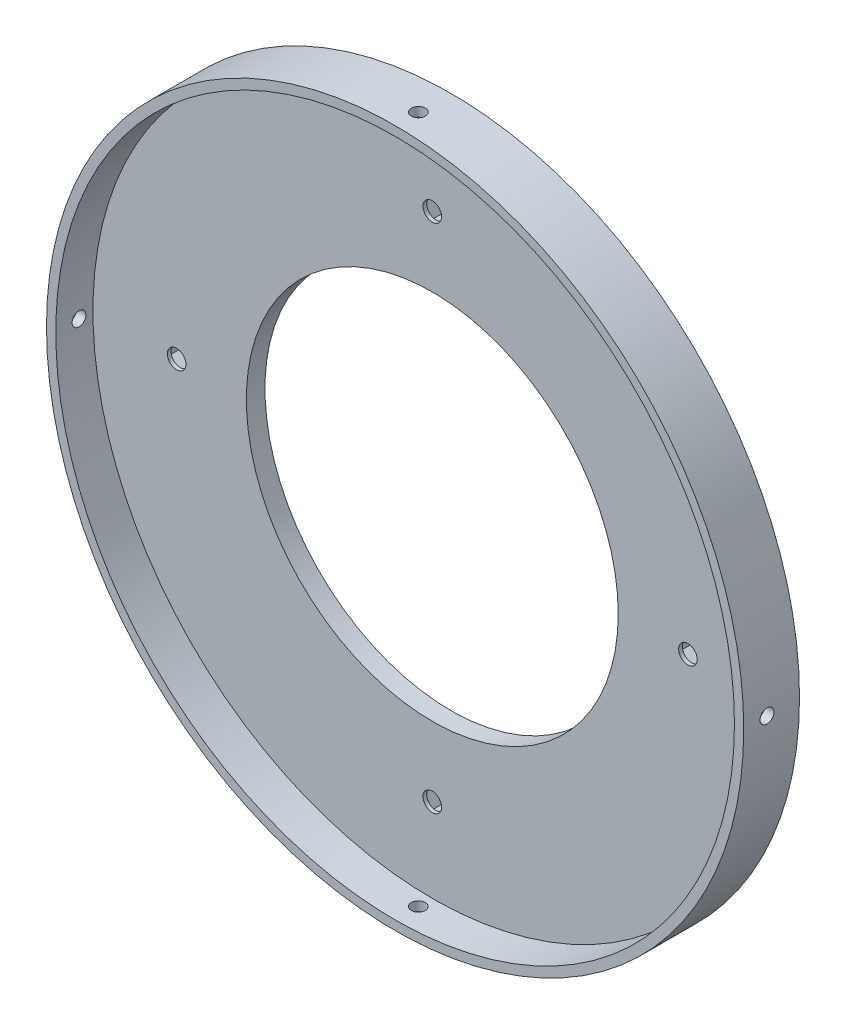
SolidWorks part; units mm, degrees
material "PET"
ref_plane "Front Plane" through (0, 0, 0) normal (0, 0, 1) x (1, 0, 0)
ref_plane "Top Plane" through (0, 0, 0) normal (0, 1, 0) x (1, 0, 0)
ref_plane "Right Plane" through (0, 0, 0) normal (1, 0, 0) x (0, 0, -1)
sketch "Sketch1" plane through (0, 0, 0) normal (0, 0, 1) x (1, 0, 0)
  circle A0 centre (0, 0) radius 75
  circle A1 centre (0, 0) radius 40
  dimension "D1" = 150
  dimension "D2" = 35
extrude "Boss-Extrude1" add sketch "Sketch1" along normal blind 4
sketch "Sketch2" plane through (0, 0, 4) normal (0, 0, 1) x (1, 0, 0)
  circle A0 centre (0, 0) radius 73
  circle A1 centre (0, 0) radius 75
  circle A2 centre (0, 0) radius 75
  dimension "D1" = 0
  dimension "D2" = 2
extrude "Boss-Extrude2" add sketch "Sketch2" along normal blind 8
sketch "Sketch3" plane through (0, 0, 0) normal (0, 1, 0) x (1, 0, 0)
  line L0 (-75, -12) -> (75, -12) construction
  circle A0 centre (0, -7) radius 1.5
  dimension "D2" = 3
  dimension "D1" = 5
extrude "Cut-Extrude1" cut sketch "Sketch3" against normal up to surface (75 mm away)
pattern_circular "CirPattern1" count 4 over 360 about axis through (0, 0, 4) along (0, 0, -1) of "Cut-Extrude1"
sketch "Sketch9" plane through (0, 0, 0) normal (0, 0, -1) x (-1, 0, 0)
  point P0 (0, 55)
  point P4 (55, 0)
  point P6 (0, -55)
  point P8 (-55, 0)
  dimension "D1" = 55
  dimension "D2" = 0
  dimension "D3" = 55
  dimension "D4" = 55
  dimension "D5" = 55
hole_wizard "Ø4.0mm Dowel Hole1" positions "Sketch9" profile "Sketch10" hole size "Ø4.0" standard "ISO" end condition through all
sketch "Sketch10" plane through (0, 55, 0) normal (1, 0, 0) x (0, 1, 0)
  line L0 (0, 0) -> (0, 12)
  line L1 (0, 12) -> (2, 12)
  line L2 (2, 12) -> (2, 0)
  line L5 (2, 0) -> (0, 0)
  line L11 (0, -6.35) -> (0, 107.95) construction
  dimension "Thru Hole Dia." = 4
  dimension "Thru Hole Depth" = 12
sketch "Sketch13" plane through (0, 0, 0) normal (0, 0, -1) x (-1, 0, 0)
  line L0 (0, 0) -> (55, 0) construction
  line L1 (4.0415, 55) -> (2.0207, 58.5)
  line L2 (2.0207, 58.5) -> (-2.0207, 58.5)
  line L3 (-2.0207, 58.5) -> (-4.0415, 55)
  line L4 (-4.0415, 55) -> (-2.0207, 51.5)
  line L5 (-2.0207, 51.5) -> (2.0207, 51.5)
  line L6 (2.0207, 51.5) -> (4.0415, 55)
  line L7 (55, -4.0415) -> (58.5, -2.0207)
  line L8 (58.5, -2.0207) -> (58.5, 2.0207)
  line L9 (58.5, 2.0207) -> (55, 4.0415)
  line L10 (55, 4.0415) -> (51.5, 2.0207)
  line L11 (51.5, 2.0207) -> (51.5, -2.0207)
  line L12 (51.5, -2.0207) -> (55, -4.0415)
  line L13 (-4.0415, -55) -> (-2.0207, -58.5)
  line L14 (-2.0207, -58.5) -> (2.0207, -58.5)
  line L15 (2.0207, -58.5) -> (4.0415, -55)
  line L16 (4.0415, -55) -> (2.0207, -51.5)
  line L17 (2.0207, -51.5) -> (-2.0207, -51.5)
  line L18 (-2.0207, -51.5) -> (-4.0415, -55)
  line L19 (-55, 4.0415) -> (-58.5, 2.0207)
  line L20 (-58.5, 2.0207) -> (-58.5, -2.0207)
  line L21 (-58.5, -2.0207) -> (-55, -4.0415)
  line L22 (-55, -4.0415) -> (-51.5, -2.0207)
  line L23 (-51.5, -2.0207) -> (-51.5, 2.0207)
  line L24 (-51.5, 2.0207) -> (-55, 4.0415)
  circle A0 centre (0, 55) radius 3.5 construction
  circle A1 centre (55, 0) radius 3.5 construction
  circle A2 centre (0, -55) radius 3.5 construction
  circle A3 centre (-55, 0) radius 3.5 construction
  point P40 (0, 0)
  dimension "D1" = 7
extrude "Cut-Extrude2" cut sketch "Sketch13" against normal blind 3.2
